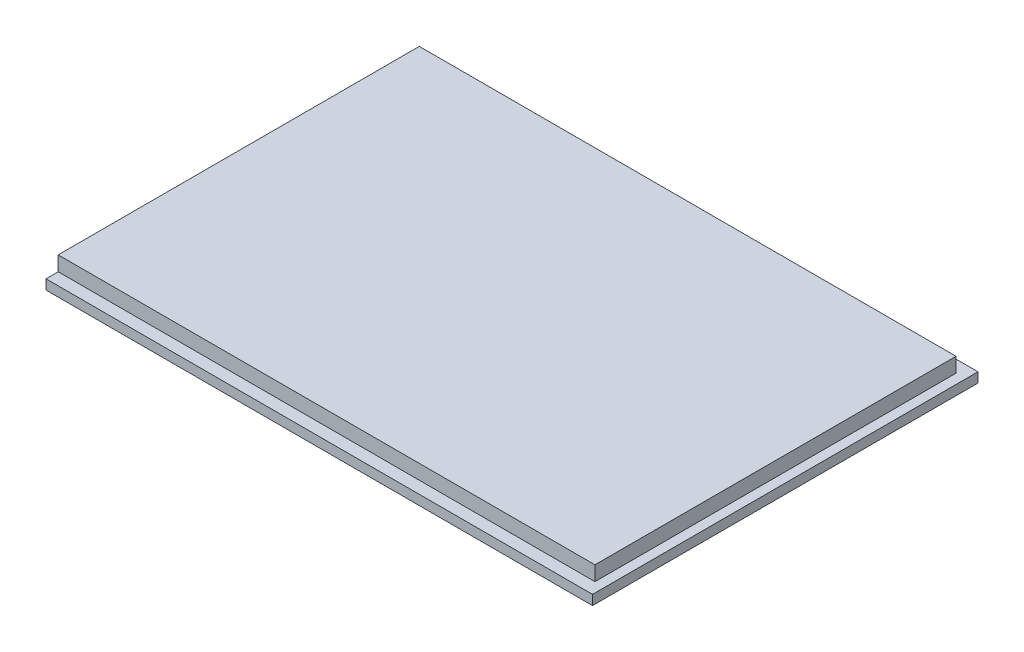
SolidWorks part; units mm, degrees
ref_plane "前视基准面" through (0, 0, 0) normal (0, 0, 1) x (1, 0, 0)
ref_plane "上视基准面" through (0, 0, 0) normal (0, 1, 0) x (1, 0, 0)
ref_plane "右视基准面" through (0, 0, 0) normal (1, 0, 0) x (0, 0, -1)
sketch "草图2" plane through (0, 0, 0) normal (0, 1, 0) x (1, 0, 0)
  line L1 (-22.4, 15.8) -> (22.4, 15.8)
  line L2 (-22.4, 15.8) -> (-22.4, -15.8)
  line L3 (-22.4, -15.8) -> (22.4, -15.8)
  line L4 (22.4, 15.8) -> (22.4, -15.8)
  line L5 (-22.4, 15.8) -> (22.4, -15.8) construction
  line L6 (-22.4, -15.8) -> (22.4, 15.8) construction
  point P0 (0, 0)
  dimension "D1" = 44.8
  dimension "D2" = 31.6
extrude "凸台-拉伸1" add sketch "草图2" along normal blind 0.8
sketch "草图3" plane through (0, 0.8, 0) normal (0, 1, 0) x (1, 0, 0)
  line L0 (-22.4, 15.8) -> (-22.4, -15.8) construction
  line L1 (-22.4, 14.8) -> (21.6, 14.8)
  line L2 (-22.4, 14.8) -> (-22.4, -14.8)
  line L3 (-22.4, -14.8) -> (21.6, -14.8)
  line L4 (21.6, 14.8) -> (21.6, -14.8)
  line L5 (22.4, 15.8) -> (-22.4, 15.8) construction
  line L6 (-22.4, -15.8) -> (22.4, -15.8) construction
  line L7 (22.4, -15.8) -> (22.4, 15.8) construction
  dimension "D1" = 1
  dimension "D2" = 1
  dimension "D3" = 0.8
extrude "凸台-拉伸2" add sketch "草图3" along normal blind 1.2
